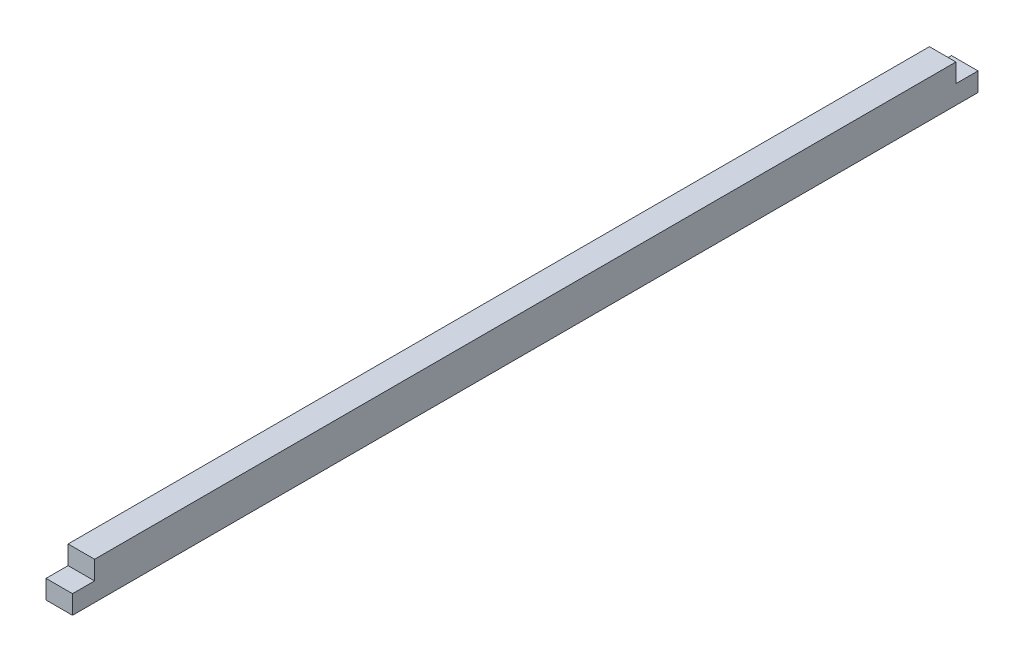
SolidWorks part; units mm, degrees
ref_plane "Front Plane" through (0, 0, 0) normal (0, 0, 1) x (1, 0, 0)
ref_plane "Top Plane" through (0, 0, 0) normal (0, 1, 0) x (1, 0, 0)
ref_plane "Right Plane" through (0, 0, 0) normal (1, 0, 0) x (0, 0, -1)
sketch "Sketch1" plane through (0, 0, 0) normal (1, 0, 0) x (0, 0, -1)
  line L1 (0, 0) -> (410, 0)
  line L2 (0, 0) -> (0, 17)
  line L3 (0, 17) -> (410, 17)
  line L4 (410, 0) -> (410, 17)
  dimension "D1" = 410
  dimension "D2" = 17
extrude "Boss-Extrude1" add sketch "Sketch1" along normal blind 12
sketch "Sketch2" plane through (12, 0, 0) normal (1, 0, 0) x (0, 0, -1)
  line L0 (205, 17) -> (205, 0) construction
  line L1 (0, 17) -> (10, 17)
  line L2 (0, 17) -> (0, 8.5)
  line L3 (0, 8.5) -> (10, 8.5)
  line L4 (10, 17) -> (10, 8.5)
  line L5 (410, 17) -> (0, 17) construction
  line L6 (0, 0) -> (410, 0) construction
  line L7 (410, 8.5) -> (400, 8.5)
  line L8 (400, 17) -> (400, 8.5)
  line L9 (410, 17) -> (400, 17)
  line L10 (410, 17) -> (410, 8.5)
  dimension "D1" = 8.5
  dimension "D2" = 10
extrude "Cut-Extrude1" cut sketch "Sketch2" against normal blind 12
